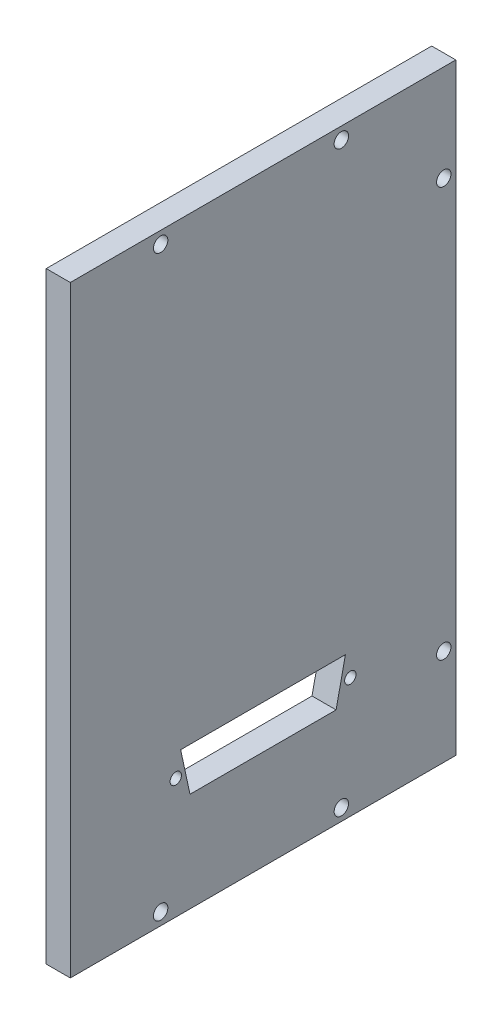
SolidWorks part; units mm, degrees
ref_plane "Front Plane" through (0, 0, 0) normal (0, 0, 1) x (1, 0, 0)
ref_plane "Top Plane" through (0, 0, 0) normal (0, 1, 0) x (1, 0, 0)
ref_plane "Right Plane" through (0, 0, 0) normal (1, 0, 0) x (0, 0, -1)
sketch "Sketch1" plane through (0, 0, 0) normal (1, 0, 0) x (0, 0, -1)
  line L1 (-50.8, -79.375) -> (50.8, -79.375)
  line L2 (-50.8, -79.375) -> (-50.8, 79.375)
  line L3 (-50.8, 79.375) -> (50.8, 79.375)
  line L4 (50.8, -79.375) -> (50.8, 79.375)
  line L5 (-50.8, -79.375) -> (50.8, 79.375) construction
  line L6 (-50.8, 79.375) -> (50.8, -79.375) construction
  point P0 (0, 0)
  dimension "D1" = 158.75
  dimension "D2" = 101.6
extrude "Boss-Extrude1" add sketch "Sketch1" along normal blind 6.35
sketch "Sketch2" plane through (6.35, 0, 0) normal (1, 0, 0) x (0, 0, -1)
  circle A3 centre (23, -47.725) radius 1.5 construction
  circle A4 centre (-23, -47.725) radius 1.5 construction
  circle A5 centre (23, -47.725) radius 1.5
  circle A6 centre (-23, -47.725) radius 1.5
extrude "Cut-Extrude1" cut sketch "Sketch2" against normal through all
sketch "Sketch3" plane through (6.35, 0, 0) normal (1, 0, 0) x (0, 0, -1)
  line L0 (18.785, -51.625) -> (20.466, -43.825) construction
  line L1 (-17.8074, -52.4143) -> (17.8074, -52.4143) construction
  line L2 (-20.466, -43.825) -> (-18.785, -51.625) construction
  line L3 (19.4885, -42.6143) -> (-19.4885, -42.6143) construction
  line L4 (18.785, -51.625) -> (20.466, -43.825) construction
  line L5 (-17.8074, -52.4143) -> (17.8074, -52.4143) construction
  line L6 (-20.466, -43.825) -> (-18.785, -51.625) construction
  line L7 (19.4885, -42.6143) -> (-19.4885, -42.6143) construction
  line L8 (-21.71, -41.8206) -> (-19.2558, -53.2081)
  line L9 (21.71, -41.8206) -> (-21.71, -41.8206)
  line L10 (19.2558, -53.2081) -> (21.71, -41.8206)
  line L11 (-19.2558, -53.2081) -> (19.2558, -53.2081)
  line L12 (19.4885, -41.8206) -> (-19.4885, -41.8206) construction
  line L13 (19.5609, -51.7922) -> (21.242, -43.9922) construction
  line L14 (-17.8074, -53.2081) -> (17.8074, -53.2081) construction
  line L15 (-21.242, -43.9922) -> (-19.5609, -51.7922) construction
  dimension "D1" = 0.7937
extrude "Cut-Extrude2" cut sketch "Sketch3" against normal through all
hole_wizard "#6 Clearance Hole1" positions "Sketch5" profile "Sketch6" hole size "#6" standard "ANSI Inch" end condition through all
sketch "Sketch5" plane through (6.35, 0, 0) normal (1, 0, 0) x (0, 0, -1)
  line L8 (-25.0825, 79.375) -> (-28.8925, 79.375)
  line L9 (-28.8925, 79.375) -> (-28.8925, 73.025)
  line L10 (-28.8925, 73.025) -> (-25.0825, 73.025)
  line L11 (-25.0825, 73.025) -> (-25.0825, 79.375)
  line L12 (-25.0825, 79.375) -> (-28.8925, 79.375) construction
  line L13 (-28.8925, 79.375) -> (-28.8925, 73.025) construction
  line L14 (-28.8925, 73.025) -> (-25.0825, 73.025) construction
  line L15 (-25.0825, 73.025) -> (-25.0825, 79.375) construction
  line L24 (22.5425, 79.375) -> (18.7325, 79.375)
  line L25 (18.7325, 79.375) -> (18.7325, 73.025)
  line L26 (18.7325, 73.025) -> (22.5425, 73.025)
  line L27 (22.5425, 73.025) -> (22.5425, 79.375)
  line L28 (22.5425, 79.375) -> (18.7325, 79.375) construction
  line L29 (18.7325, 79.375) -> (18.7325, 73.025) construction
  line L30 (18.7325, 73.025) -> (22.5425, 73.025) construction
  line L31 (22.5425, 73.025) -> (22.5425, 79.375) construction
  line L32 (-28.8925, 79.375) -> (-25.0825, 73.025) construction
  line L34 (18.7325, 79.375) -> (22.5425, 73.025) construction
  line L59 (22.5425, -73.025) -> (18.7325, -73.025) construction
  line L60 (18.7325, -73.025) -> (18.7325, -79.375) construction
  line L61 (18.7325, -79.375) -> (22.5425, -79.375) construction
  line L62 (22.5425, -79.375) -> (22.5425, -73.025) construction
  line L63 (-25.0825, -73.025) -> (-28.8925, -73.025) construction
  line L64 (-28.8925, -73.025) -> (-28.8925, -79.375) construction
  line L65 (-28.8925, -79.375) -> (-25.0825, -79.375) construction
  line L66 (-25.0825, -79.375) -> (-25.0825, -73.025) construction
  line L67 (22.5425, -73.025) -> (18.7325, -73.025) construction
  line L68 (18.7325, -73.025) -> (18.7325, -79.375) construction
  line L69 (18.7325, -79.375) -> (22.5425, -79.375) construction
  line L70 (22.5425, -79.375) -> (22.5425, -73.025) construction
  line L71 (-25.0825, -73.025) -> (-28.8925, -73.025) construction
  line L72 (-28.8925, -73.025) -> (-28.8925, -79.375) construction
  line L73 (-28.8925, -79.375) -> (-25.0825, -79.375) construction
  line L74 (-25.0825, -79.375) -> (-25.0825, -73.025) construction
  line L75 (-28.8925, -73.025) -> (-25.0825, -79.375) construction
  line L77 (18.7325, -73.025) -> (22.5425, -79.375) construction
  line L78 (44.45, -52.07) -> (44.45, -55.88) construction
  line L79 (44.45, -55.88) -> (50.8, -55.88) construction
  line L80 (50.8, -55.88) -> (50.8, -52.07) construction
  line L81 (50.8, -52.07) -> (44.45, -52.07) construction
  line L82 (44.45, 55.88) -> (44.45, 52.07) construction
  line L83 (44.45, 52.07) -> (50.8, 52.07) construction
  line L84 (50.8, 52.07) -> (50.8, 55.88) construction
  line L85 (50.8, 55.88) -> (44.45, 55.88) construction
  line L86 (44.45, -52.07) -> (44.45, -55.88) construction
  line L87 (44.45, -55.88) -> (50.8, -55.88) construction
  line L88 (50.8, -55.88) -> (50.8, -52.07) construction
  line L89 (50.8, -52.07) -> (44.45, -52.07) construction
  line L90 (44.45, 55.88) -> (44.45, 52.07) construction
  line L91 (44.45, 52.07) -> (50.8, 52.07) construction
  line L92 (50.8, 52.07) -> (50.8, 55.88) construction
  line L93 (50.8, 55.88) -> (44.45, 55.88) construction
  line L94 (44.45, 55.88) -> (50.8, 52.07) construction
  line L96 (44.45, -52.07) -> (50.8, -55.88) construction
  point P44 (-26.9875, 76.2)
  point P46 (20.6375, 76.2)
  point P124 (-26.9875, -76.2)
  point P126 (20.6375, -76.2)
  point P187 (47.625, 53.975)
  point P189 (47.625, -53.975)
  dimension "D1" = 0
  dimension "D2" = 0
sketch "Sketch6" plane through (6.35, -53.975, -47.625) normal (0, 1, 0) x (0, 0, -1)
  line L0 (0, 0) -> (0, 6.35)
  line L1 (0, 6.35) -> (1.8986, 6.35)
  line L2 (1.8986, 6.35) -> (1.8986, 0)
  line L5 (1.8986, 0) -> (0, 0)
  line L11 (0, -6.35) -> (0, 107.95) construction
  dimension "Thru Hole Dia." = 3.7973
  dimension "Thru Hole Depth" = 6.35
